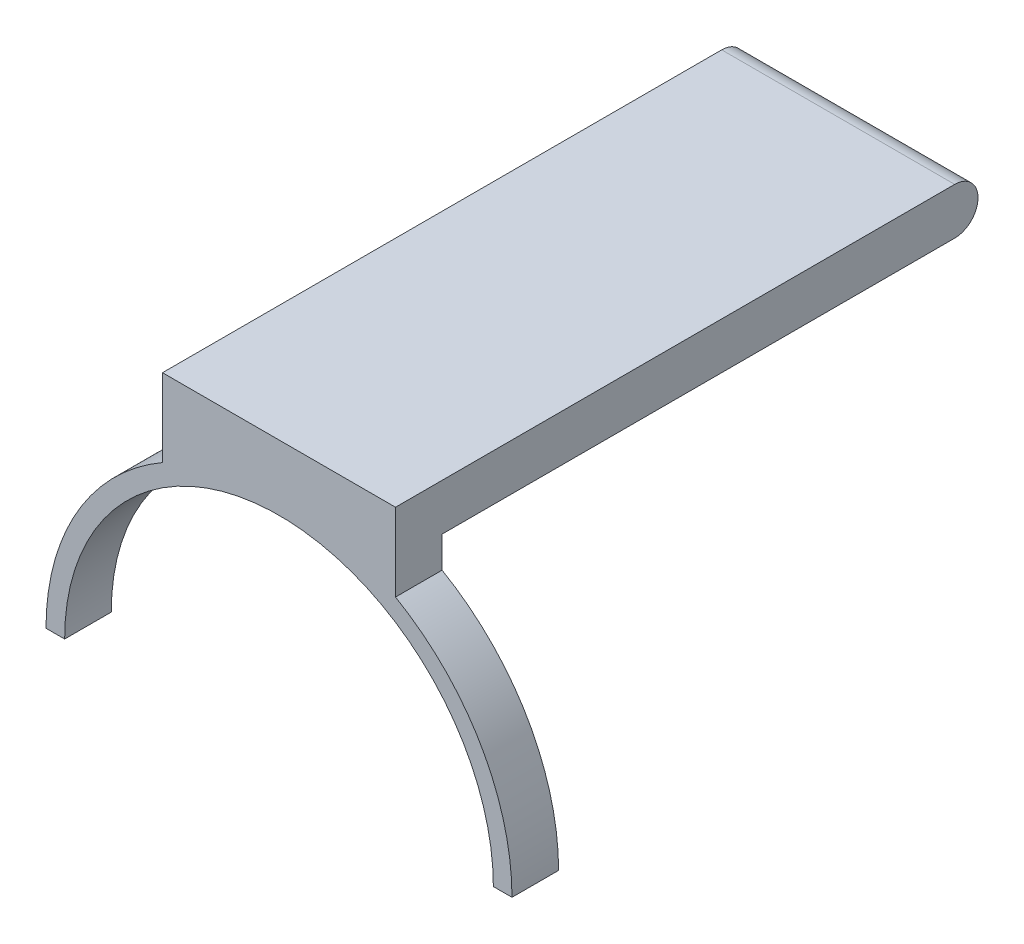
SolidWorks part; units mm, degrees
ref_plane "Front" through (0, 0, 0) normal (0, 0, 1) x (1, 0, 0)
ref_plane "Top" through (0, 0, 0) normal (0, 1, 0) x (1, 0, 0)
ref_plane "Right" through (0, 0, 0) normal (1, 0, 0) x (0, 0, -1)
sketch "草图1" plane through (0, 0, 0) normal (0, 0, 1) x (1, 0, 0)
  line L0 (-23.0866, 0) -> (0, 0) construction
  line L1 (0, 0) -> (0, 28.5445) construction
  line L3 (-25, 5) -> (25, 5)
  line L4 (-25, 5) -> (-25, -5)
  line L5 (-25, -5) -> (25, -5)
  line L6 (25, 5) -> (25, -5)
  dimension "D1" = 50
  dimension "D2" = 10
  dimension "D3" = 5
  dimension "D4" = 25
extrude "凸台-拉伸1" add sketch "草图1" along normal blind 120
sketch "草图2" plane through (25, 0, 0) normal (1, 0, 0) x (0, 0, -1)
  circle A0 centre (0, 0) radius 5
sketch "草图3" plane through (0, 0, 120) normal (0, 0, 1) x (1, 0, 0)
  line L0 (0, 5) -> (0, -98.1891) construction
  line L1 (25, 5) -> (-25, 5) construction
  line L2 (0, -5) -> (25, -5) construction
  line L3 (-50, -55) -> (-46, -55)
  line L4 (-25, -5) -> (-25, -11.6987)
  line L5 (25, -5) -> (25, -11.6987)
  line L6 (46, -55) -> (50, -55)
  line L7 (-25, -5) -> (25, -5)
  arc A0 (50, -55) -> (25, -11.6987) centre (0, -55) ccw
  arc A1 (46, -55) -> (-46, -55) centre (0, -55) ccw
  arc A2 (-25, -11.6987) -> (-50, -55) centre (0, -55) ccw
  dimension "D1" = 50
extrude "凸台-拉伸2" add sketch "草图3" against normal blind 10
extrude "凸台-拉伸3" add sketch "草图2" against normal blind 50
